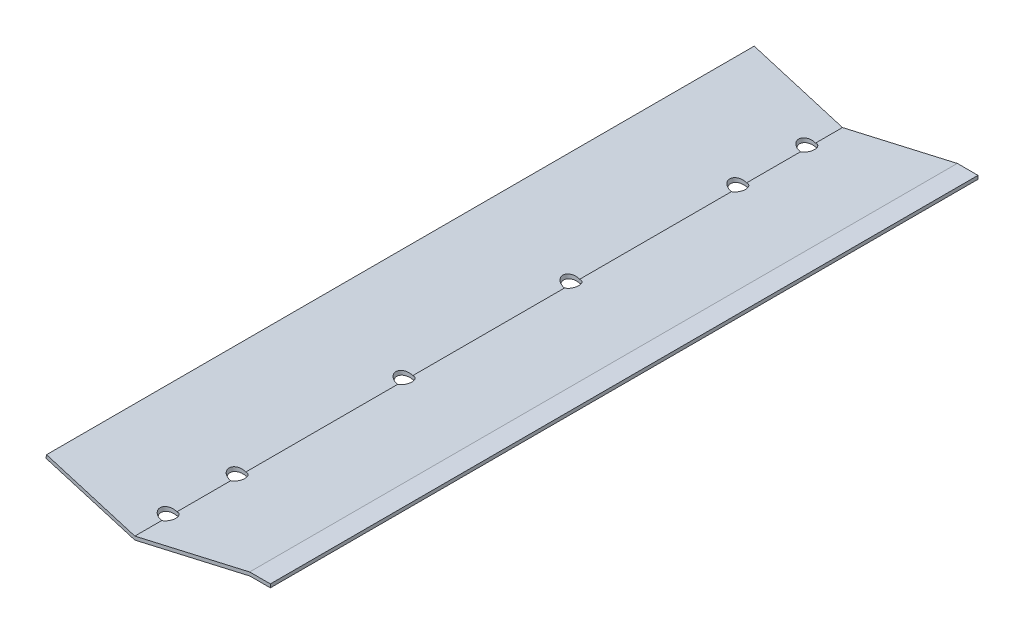
SolidWorks part; units mm, degrees
material "ASTM A36 Steel"
ref_plane "Front Plane" through (0, 0, 0) normal (0, 0, 1) x (1, 0, 0)
ref_plane "Top Plane" through (0, 0, 0) normal (0, 1, 0) x (1, 0, 0)
ref_plane "Right Plane" through (0, 0, 0) normal (1, 0, 0) x (0, 0, -1)
sketch "Sketch1" plane through (0, 0, 0) normal (0, 0, 1) x (1, 0, 0)
  line L0 (-11592.2884, 7313.5904) -> (-11721.0968, 7351.9332)
  line L1 (-11721.0968, 7351.9332) -> (-11720.2884, 7356.8675)
  line L2 (-11720.2884, 7356.8675) -> (-11592.2884, 7318.6571)
  line L3 (-11592.2884, 7318.6571) -> (-11425.7884, 7356.8675)
  line L4 (-11425.7884, 7356.8675) -> (-11395.7884, 7356.8675)
  line L5 (-11395.7884, 7356.8675) -> (-11395.7884, 7351.8675)
  line L6 (-11395.7884, 7351.8675) -> (-11425.3816, 7351.8675)
  line L7 (-11425.3816, 7351.8675) -> (-11592.2884, 7313.5904)
extrude "Boss-Extrude1" add sketch "Sketch1" along normal blind 1026
sketch "Sketch2" plane through (-2172.6475, 9473.8142, 0) normal (0.2235, -0.9747, 0) x (0.9747, 0.2235, 0)
  line L0 (-9664.1711, 1026) -> (-9664.1711, 0) construction
  line L1 (-9781.1495, 0) -> (-9664.1711, 0) construction
  circle A0 centre (-9664.1711, 50) radius 11
  circle A1 centre (-9664.1711, 150) radius 11
  circle A2 centre (-9664.1711, 392) radius 11
  circle A4 centre (-9664.1711, 876) radius 11
  circle A5 centre (-9664.1711, 976) radius 11
  circle A6 centre (-9664.1711, 634) radius 11
  dimension "D1" = 22
  dimension "D2" = 50
  dimension "D3" = 22
  dimension "D4" = 100
  dimension "D5" = 22
  dimension "D6" = 22
  dimension "D7" = 22
  dimension "D8" = 22
  dimension "D9" = 242
  dimension "D10" = 242
  dimension "D11" = 242
  dimension "D12" = 100
extrude "Cut-Extrude1" cut sketch "Sketch2" against normal through all both and the other way through all
